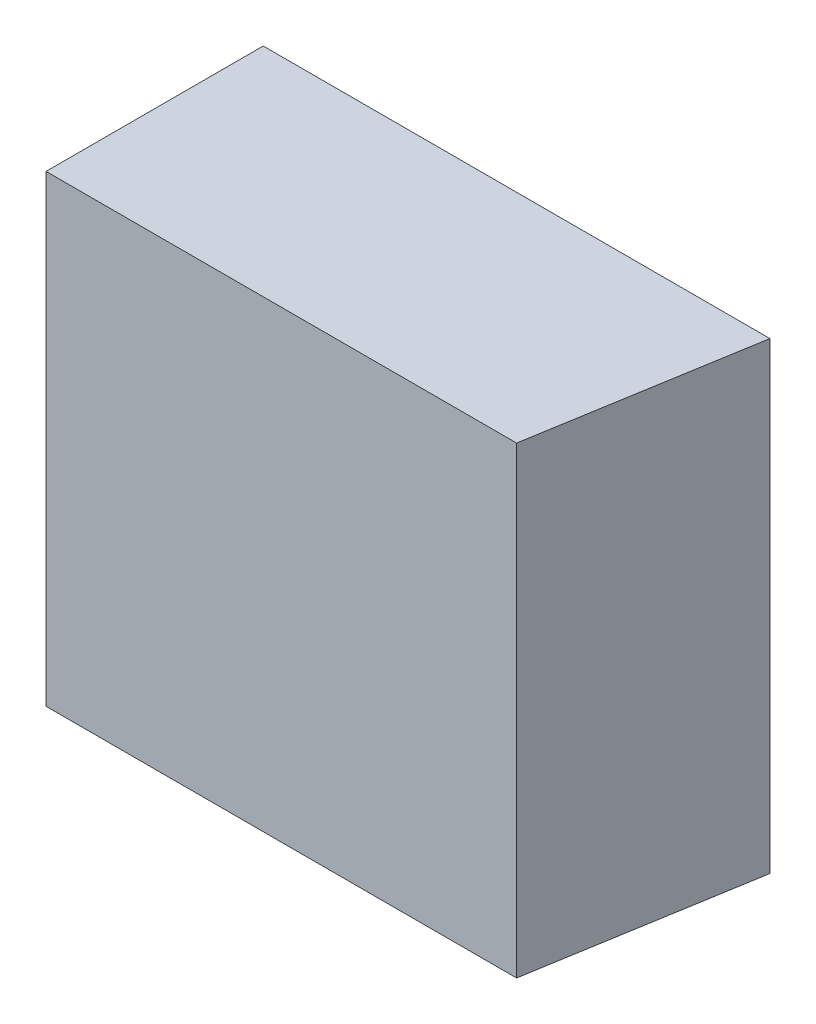
SolidWorks part; units mm, degrees
ref_plane "前视基准面" through (0, 0, 0) normal (0, 0, 1) x (1, 0, 0)
ref_plane "上视基准面" through (0, 0, 0) normal (0, 1, 0) x (1, 0, 0)
ref_plane "右视基准面" through (0, 0, 0) normal (1, 0, 0) x (0, 0, -1)
other "Configuration Table"
sketch "草图1" plane through (0, 0, 0) normal (0, 1, 0) x (1, 0, 0)
  line L5 (200, 0) -> (0, 0)
  line L7 (-150, -150) -> (175, -150)
  line L8 (175, -150) -> (200, 0)
  line L10 (-150, -150) -> (-150, 0)
  line L11 (0, 0) -> (-150, 0)
  point P0 (0, 0)
  dimension "D1" = 350
extrude "凸台-拉伸2" add sketch "草图1" along normal mid plane 320 contours L5 L11 L10 L7 L8
shell "抽壳2" thickness 4
